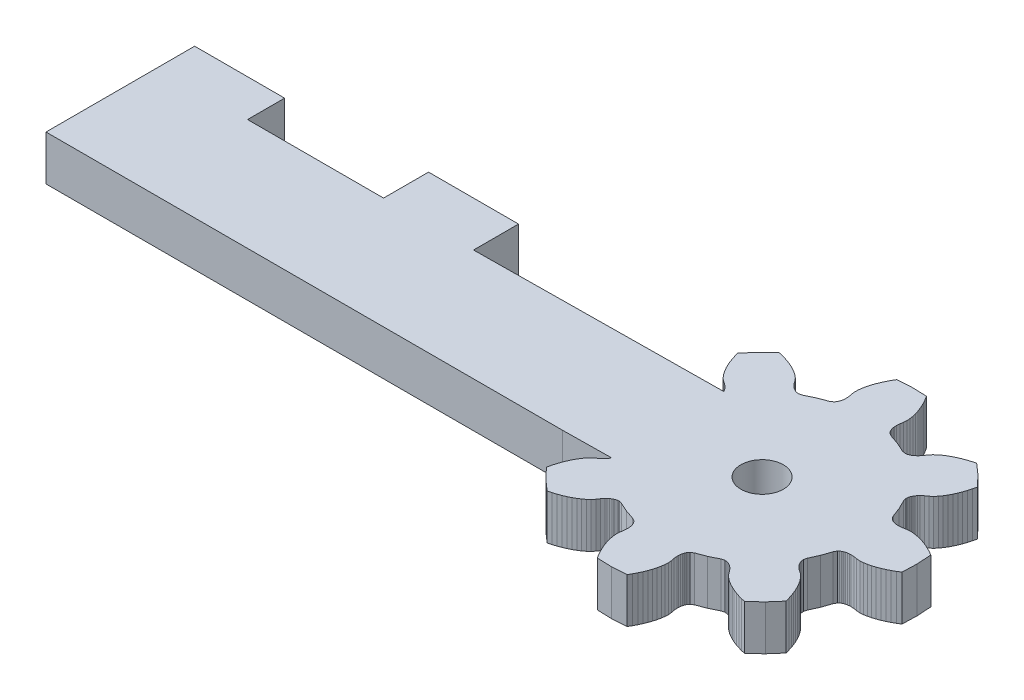
SolidWorks part; units mm, degrees
ref_plane "Front Plane" through (0, 0, 0) normal (0, 0, 1) x (1, 0, 0)
ref_plane "Top Plane" through (0, 0, 0) normal (0, 1, 0) x (1, 0, 0)
ref_plane "Right Plane" through (0, 0, 0) normal (1, 0, 0) x (0, 0, -1)
sketch "Sketch1" plane through (0, 0, 0) normal (0, 1, 0) x (1, 0, 0)
  line L0 (63.4907, 166.1354) -> (63.4907, 169.3104)
  line L1 (63.4907, 169.3104) -> (57.1407, 169.3104)
  line L2 (57.1407, 169.3104) -> (57.1407, 166.1354)
  line L3 (57.1407, 166.1354) -> (47.5407, 166.1354)
  line L4 (47.5407, 166.1354) -> (47.5407, 168.7529)
  line L5 (47.5407, 168.7529) -> (41.1907, 168.7529)
  line L6 (41.1907, 168.7529) -> (41.1907, 158.2613)
  line L7 (41.1907, 158.2613) -> (77.6477, 158.2613)
  line L1268 (81.0578, 158.2714) -> (81.0243, 158.3054)
  line L1269 (81.0243, 158.3054) -> (77.6477, 158.2613)
  line L1276 (63.4907, 166.1354) -> (80.9763, 166.3177)
  line L1277 (80.9763, 166.3177) -> (80.9618, 166.3272)
  line L1278 (80.9618, 166.3272) -> (80.9303, 166.3857)
  line L1279 (80.9303, 166.3857) -> (80.8605, 166.4907)
  line L1280 (80.8605, 166.4907) -> (80.7838, 166.5839)
  line L1281 (80.7838, 166.5839) -> (80.7017, 166.668)
  line L1282 (80.7017, 166.668) -> (80.5246, 166.8149)
  line L1283 (80.5246, 166.8149) -> (80.3334, 166.9392)
  line L1284 (80.3334, 166.9392) -> (80.1557, 167.0849)
  line L1285 (80.1557, 167.0849) -> (79.9967, 167.2599)
  line L1286 (79.9967, 167.2599) -> (79.8501, 167.4532)
  line L1287 (79.8501, 167.4532) -> (79.7145, 167.6617)
  line L1288 (79.7145, 167.6617) -> (79.5894, 167.8837)
  line L1289 (79.5894, 167.8837) -> (79.4745, 168.1179)
  line L1290 (79.4745, 168.1179) -> (79.3699, 168.3635)
  line L1291 (79.3699, 168.3635) -> (79.2754, 168.6197)
  line L1292 (79.2754, 168.6197) -> (79.1915, 168.886)
  line L1293 (79.1915, 168.886) -> (79.1181, 169.1617)
  line L1294 (79.1181, 169.1617) -> (79.8009, 169.9374)
  line L1295 (79.8009, 169.9374) -> (80.5548, 170.6443)
  line L1296 (80.5548, 170.6443) -> (80.8327, 170.5796)
  line L1297 (80.8327, 170.5796) -> (81.1014, 170.504)
  line L1298 (81.1014, 170.504) -> (81.3605, 170.4177)
  line L1299 (81.3605, 170.4177) -> (81.6093, 170.3208)
  line L1300 (81.6093, 170.3208) -> (81.847, 170.2133)
  line L1301 (81.847, 170.2133) -> (82.0728, 170.0952)
  line L1302 (82.0728, 170.0952) -> (82.2854, 169.9663)
  line L1303 (82.2854, 169.9663) -> (82.4832, 169.8259)
  line L1304 (82.4832, 169.8259) -> (82.6631, 169.6724)
  line L1305 (82.6631, 169.6724) -> (82.8144, 169.4994)
  line L1306 (82.8144, 169.4994) -> (82.9446, 169.3122)
  line L1307 (82.9446, 169.3122) -> (83.097, 169.1398)
  line L1308 (83.097, 169.1398) -> (83.1836, 169.0603)
  line L1309 (83.1836, 169.0603) -> (83.2792, 168.9866)
  line L1310 (83.2792, 168.9866) -> (83.3864, 168.9201)
  line L1311 (83.3864, 168.9201) -> (83.4458, 168.8905)
  line L1312 (83.4458, 168.8905) -> (83.5105, 168.8639)
  line L1313 (83.5105, 168.8639) -> (83.5824, 168.8415)
  line L1314 (83.5824, 168.8415) -> (83.6651, 168.8253)
  line L1315 (83.6651, 168.8253) -> (83.768, 168.8205)
  line L1316 (83.768, 168.8205) -> (83.9876, 168.8804)
  line L1317 (83.9876, 168.8804) -> (84.6212, 169.1914)
  line L1318 (84.6212, 169.1914) -> (85.2815, 169.4403)
  line L1319 (85.2815, 169.4403) -> (85.4756, 169.5595)
  line L1320 (85.4756, 169.5595) -> (85.5425, 169.6378)
  line L1321 (85.5425, 169.6378) -> (85.5873, 169.7091)
  line L1322 (85.5873, 169.7091) -> (85.6202, 169.7768)
  line L1323 (85.6202, 169.7768) -> (85.6451, 169.8422)
  line L1324 (85.6451, 169.8422) -> (85.6641, 169.9058)
  line L1325 (85.6641, 169.9058) -> (85.6891, 170.0295)
  line L1326 (85.6891, 170.0295) -> (85.7007, 170.1496)
  line L1327 (85.7007, 170.1496) -> (85.7022, 170.2671)
  line L1328 (85.7022, 170.2671) -> (85.6808, 170.4962)
  line L1329 (85.6808, 170.4962) -> (85.6334, 170.7193)
  line L1330 (85.6334, 170.7193) -> (85.6109, 170.948)
  line L1331 (85.6109, 170.948) -> (85.6222, 171.1842)
  line L1332 (85.6222, 171.1842) -> (85.6552, 171.4245)
  line L1333 (85.6552, 171.4245) -> (85.7068, 171.6678)
  line L1334 (85.7068, 171.6678) -> (85.7752, 171.9132)
  line L1335 (85.7752, 171.9132) -> (85.8596, 172.1601)
  line L1336 (85.8596, 172.1601) -> (85.9593, 172.4078)
  line L1337 (85.9593, 172.4078) -> (86.0737, 172.6557)
  line L1338 (86.0737, 172.6557) -> (86.2026, 172.9034)
  line L1339 (86.2026, 172.9034) -> (86.3457, 173.1502)
  line L1340 (86.3457, 173.1502) -> (87.377, 173.2159)
  line L1341 (87.377, 173.2159) -> (88.4099, 173.1826)
  line L1342 (88.4099, 173.1826) -> (88.5607, 172.9404)
  line L1343 (88.5607, 172.9404) -> (88.6973, 172.6969)
  line L1344 (88.6973, 172.6969) -> (88.8195, 172.4527)
  line L1345 (88.8195, 172.4527) -> (88.9268, 172.2082)
  line L1346 (88.9268, 172.2082) -> (89.0189, 171.9642)
  line L1347 (89.0189, 171.9642) -> (89.0951, 171.721)
  line L1348 (89.0951, 171.721) -> (89.1543, 171.4795)
  line L1349 (89.1543, 171.4795) -> (89.1948, 171.2403)
  line L1350 (89.1948, 171.2403) -> (89.2136, 171.0046)
  line L1351 (89.2136, 171.0046) -> (89.1981, 170.7753)
  line L1352 (89.1981, 170.7753) -> (89.1579, 170.5508)
  line L1353 (89.1579, 170.5508) -> (89.1437, 170.3212)
  line L1354 (89.1437, 170.3212) -> (89.1488, 170.2038)
  line L1355 (89.1488, 170.2038) -> (89.1642, 170.0841)
  line L1356 (89.1642, 170.0841) -> (89.193, 169.9613)
  line L1357 (89.193, 169.9613) -> (89.214, 169.8982)
  line L1358 (89.214, 169.8982) -> (89.241, 169.8337)
  line L1359 (89.241, 169.8337) -> (89.276, 169.7671)
  line L1360 (89.276, 169.7671) -> (89.3231, 169.6971)
  line L1361 (89.3231, 169.6971) -> (89.3924, 169.621)
  line L1362 (89.3924, 169.621) -> (89.59, 169.508)
  line L1363 (89.59, 169.508) -> (90.2579, 169.28)
  line L1364 (90.2579, 169.28) -> (90.9009, 168.989)
  line L1365 (90.9009, 168.989) -> (91.1223, 168.9361)
  line L1366 (91.1223, 168.9361) -> (91.225, 168.9441)
  line L1367 (91.225, 168.9441) -> (91.3072, 168.9629)
  line L1368 (91.3072, 168.9629) -> (91.3783, 168.9875)
  line L1369 (91.3783, 168.9875) -> (91.4422, 169.0161)
  line L1370 (91.4422, 169.0161) -> (91.5006, 169.0476)
  line L1371 (91.5006, 169.0476) -> (91.6057, 169.1174)
  line L1372 (91.6057, 169.1174) -> (91.6989, 169.1941)
  line L1373 (91.6989, 169.1941) -> (91.7829, 169.2762)
  line L1374 (91.7829, 169.2762) -> (91.9298, 169.4533)
  line L1375 (91.9298, 169.4533) -> (92.0541, 169.6445)
  line L1376 (92.0541, 169.6445) -> (92.1999, 169.8223)
  line L1377 (92.1999, 169.8223) -> (92.3749, 169.9812)
  line L1378 (92.3749, 169.9812) -> (92.5682, 170.1278)
  line L1379 (92.5682, 170.1278) -> (92.7767, 170.2634)
  line L1380 (92.7767, 170.2634) -> (92.9986, 170.3885)
  line L1381 (92.9986, 170.3885) -> (93.2328, 170.5034)
  line L1382 (93.2328, 170.5034) -> (93.4784, 170.6081)
  line L1383 (93.4784, 170.6081) -> (93.7347, 170.7025)
  line L1384 (93.7347, 170.7025) -> (94.001, 170.7864)
  line L1385 (94.001, 170.7864) -> (94.2766, 170.8598)
  line L1386 (94.2766, 170.8598) -> (95.0524, 170.177)
  line L1387 (95.0524, 170.177) -> (95.7592, 169.4231)
  line L1388 (95.7592, 169.4231) -> (95.6945, 169.1453)
  line L1389 (95.6945, 169.1453) -> (95.6189, 168.8765)
  line L1390 (95.6189, 168.8765) -> (95.5327, 168.6174)
  line L1391 (95.5327, 168.6174) -> (95.4357, 168.3686)
  line L1392 (95.4357, 168.3686) -> (95.3283, 168.1309)
  line L1393 (95.3283, 168.1309) -> (95.2102, 167.9051)
  line L1394 (95.2102, 167.9051) -> (95.0812, 167.6925)
  line L1395 (95.0812, 167.6925) -> (94.9408, 167.4947)
  line L1396 (94.9408, 167.4947) -> (94.7874, 167.3148)
  line L1397 (94.7874, 167.3148) -> (94.6144, 167.1635)
  line L1398 (94.6144, 167.1635) -> (94.4271, 167.0333)
  line L1399 (94.4271, 167.0333) -> (94.2547, 166.8809)
  line L1400 (94.2547, 166.8809) -> (94.1753, 166.7943)
  line L1401 (94.1753, 166.7943) -> (94.1016, 166.6988)
  line L1402 (94.1016, 166.6988) -> (94.0351, 166.5915)
  line L1403 (94.0351, 166.5915) -> (94.0054, 166.5321)
  line L1404 (94.0054, 166.5321) -> (93.9788, 166.4674)
  line L1405 (93.9788, 166.4674) -> (93.9565, 166.3955)
  line L1406 (93.9565, 166.3955) -> (93.9403, 166.3128)
  line L1407 (93.9403, 166.3128) -> (93.9355, 166.21)
  line L1408 (93.9355, 166.21) -> (93.9954, 165.9903)
  line L1409 (93.9954, 165.9903) -> (94.3064, 165.3568)
  line L1410 (94.3064, 165.3568) -> (94.5553, 164.6964)
  line L1411 (94.5553, 164.6964) -> (94.6744, 164.5024)
  line L1412 (94.6744, 164.5024) -> (94.7527, 164.4354)
  line L1413 (94.7527, 164.4354) -> (94.824, 164.3906)
  line L1414 (94.824, 164.3906) -> (94.8918, 164.3578)
  line L1415 (94.8918, 164.3578) -> (94.9571, 164.3328)
  line L1416 (94.9571, 164.3328) -> (95.0208, 164.3138)
  line L1417 (95.0208, 164.3138) -> (95.1444, 164.2888)
  line L1418 (95.1444, 164.2888) -> (95.2645, 164.2772)
  line L1419 (95.2645, 164.2772) -> (95.382, 164.2758)
  line L1420 (95.382, 164.2758) -> (95.6112, 164.2972)
  line L1421 (95.6112, 164.2972) -> (95.8342, 164.3445)
  line L1422 (95.8342, 164.3445) -> (96.063, 164.3671)
  line L1423 (96.063, 164.3671) -> (96.2992, 164.3557)
  line L1424 (96.2992, 164.3557) -> (96.5395, 164.3227)
  line L1425 (96.5395, 164.3227) -> (96.7828, 164.2712)
  line L1426 (96.7828, 164.2712) -> (97.0282, 164.2027)
  line L1427 (97.0282, 164.2027) -> (97.275, 164.1183)
  line L1428 (97.275, 164.1183) -> (97.5227, 164.0186)
  line L1429 (97.5227, 164.0186) -> (97.7707, 163.9042)
  line L1430 (97.7707, 163.9042) -> (98.0183, 163.7753)
  line L1431 (98.0183, 163.7753) -> (98.2652, 163.6323)
  line L1432 (98.2652, 163.6323) -> (98.3308, 162.6009)
  line L1433 (98.3308, 162.6009) -> (98.2976, 161.568)
  line L1434 (98.2976, 161.568) -> (98.0554, 161.4173)
  line L1435 (98.0554, 161.4173) -> (97.8119, 161.2806)
  line L1436 (97.8119, 161.2806) -> (97.5677, 161.1585)
  line L1437 (97.5677, 161.1585) -> (97.3232, 161.0511)
  line L1438 (97.3232, 161.0511) -> (97.0791, 160.959)
  line L1439 (97.0791, 160.959) -> (96.836, 160.8829)
  line L1440 (96.836, 160.8829) -> (96.5944, 160.8237)
  line L1441 (96.5944, 160.8237) -> (96.3553, 160.7831)
  line L1442 (96.3553, 160.7831) -> (96.1196, 160.7644)
  line L1443 (96.1196, 160.7644) -> (95.8903, 160.7798)
  line L1444 (95.8903, 160.7798) -> (95.6658, 160.8201)
  line L1445 (95.6658, 160.8201) -> (95.4361, 160.8342)
  line L1446 (95.4361, 160.8342) -> (95.3187, 160.8291)
  line L1447 (95.3187, 160.8291) -> (95.199, 160.8137)
  line L1448 (95.199, 160.8137) -> (95.0762, 160.7849)
  line L1449 (95.0762, 160.7849) -> (95.0132, 160.7639)
  line L1450 (95.0132, 160.7639) -> (94.9487, 160.7369)
  line L1451 (94.9487, 160.7369) -> (94.882, 160.7019)
  line L1452 (94.882, 160.7019) -> (94.8121, 160.6549)
  line L1453 (94.8121, 160.6549) -> (94.736, 160.5855)
  line L1454 (94.736, 160.5855) -> (94.623, 160.3879)
  line L1455 (94.623, 160.3879) -> (94.3949, 159.72)
  line L1456 (94.3949, 159.72) -> (94.1039, 159.077)
  line L1457 (94.1039, 159.077) -> (94.051, 158.8556)
  line L1458 (94.051, 158.8556) -> (94.0591, 158.7529)
  line L1459 (94.0591, 158.7529) -> (94.0778, 158.6708)
  line L1460 (94.0778, 158.6708) -> (94.1025, 158.5996)
  line L1461 (94.1025, 158.5996) -> (94.131, 158.5358)
  line L1462 (94.131, 158.5358) -> (94.1626, 158.4773)
  line L1463 (94.1626, 158.4773) -> (94.2324, 158.3722)
  line L1464 (94.2324, 158.3722) -> (94.3091, 158.2791)
  line L1465 (94.3091, 158.2791) -> (94.3912, 158.195)
  line L1466 (94.3912, 158.195) -> (94.5683, 158.0481)
  line L1467 (94.5683, 158.0481) -> (94.7595, 157.9238)
  line L1468 (94.7595, 157.9238) -> (94.9372, 157.778)
  line L1469 (94.9372, 157.778) -> (95.0962, 157.603)
  line L1470 (95.0962, 157.603) -> (95.2427, 157.4097)
  line L1471 (95.2427, 157.4097) -> (95.3783, 157.2013)
  line L1472 (95.3783, 157.2013) -> (95.5035, 156.9793)
  line L1473 (95.5035, 156.9793) -> (95.6184, 156.7451)
  line L1474 (95.6184, 156.7451) -> (95.723, 156.4995)
  line L1475 (95.723, 156.4995) -> (95.8174, 156.2432)
  line L1476 (95.8174, 156.2432) -> (95.9014, 155.9769)
  line L1477 (95.9014, 155.9769) -> (95.9748, 155.7013)
  line L1478 (95.9748, 155.7013) -> (95.292, 154.9255)
  line L1479 (95.292, 154.9255) -> (94.5381, 154.2187)
  line L1480 (94.5381, 154.2187) -> (94.2602, 154.2834)
  line L1481 (94.2602, 154.2834) -> (93.9914, 154.359)
  line L1482 (93.9914, 154.359) -> (93.7324, 154.4453)
  line L1483 (93.7324, 154.4453) -> (93.4836, 154.5422)
  line L1484 (93.4836, 154.5422) -> (93.2458, 154.6496)
  line L1485 (93.2458, 154.6496) -> (93.0201, 154.7677)
  line L1486 (93.0201, 154.7677) -> (92.8074, 154.8967)
  line L1487 (92.8074, 154.8967) -> (92.6097, 155.0371)
  line L1488 (92.6097, 155.0371) -> (92.4297, 155.1905)
  line L1489 (92.4297, 155.1905) -> (92.2785, 155.3636)
  line L1490 (92.2785, 155.3636) -> (92.1482, 155.5508)
  line L1491 (92.1482, 155.5508) -> (91.9959, 155.7232)
  line L1492 (91.9959, 155.7232) -> (91.9092, 155.8026)
  line L1493 (91.9092, 155.8026) -> (91.8137, 155.8763)
  line L1494 (91.8137, 155.8763) -> (91.7065, 155.9428)
  line L1495 (91.7065, 155.9428) -> (91.6471, 155.9725)
  line L1496 (91.6471, 155.9725) -> (91.5824, 155.9991)
  line L1497 (91.5824, 155.9991) -> (91.5105, 156.0215)
  line L1498 (91.5105, 156.0215) -> (91.4278, 156.0376)
  line L1499 (91.4278, 156.0376) -> (91.3249, 156.0424)
  line L1500 (91.3249, 156.0424) -> (91.1052, 155.9826)
  line L1501 (91.1052, 155.9826) -> (90.4717, 155.6716)
  line L1502 (90.4717, 155.6716) -> (89.8113, 155.4226)
  line L1503 (89.8113, 155.4226) -> (89.6173, 155.3035)
  line L1504 (89.6173, 155.3035) -> (89.5504, 155.2252)
  line L1505 (89.5504, 155.2252) -> (89.5056, 155.1539)
  line L1506 (89.5056, 155.1539) -> (89.4727, 155.0862)
  line L1507 (89.4727, 155.0862) -> (89.4478, 155.0208)
  line L1508 (89.4478, 155.0208) -> (89.4287, 154.9571)
  line L1509 (89.4287, 154.9571) -> (89.4038, 154.8335)
  line L1510 (89.4038, 154.8335) -> (89.3921, 154.7134)
  line L1511 (89.3921, 154.7134) -> (89.3907, 154.5959)
  line L1512 (89.3907, 154.5959) -> (89.4121, 154.3667)
  line L1513 (89.4121, 154.3667) -> (89.4594, 154.1437)
  line L1514 (89.4594, 154.1437) -> (89.482, 153.9149)
  line L1515 (89.482, 153.9149) -> (89.4707, 153.6788)
  line L1516 (89.4707, 153.6788) -> (89.4377, 153.4385)
  line L1517 (89.4377, 153.4385) -> (89.3861, 153.1952)
  line L1518 (89.3861, 153.1952) -> (89.3176, 152.9497)
  line L1519 (89.3176, 152.9497) -> (89.2332, 152.7029)
  line L1520 (89.2332, 152.7029) -> (89.1336, 152.4552)
  line L1521 (89.1336, 152.4552) -> (89.0191, 152.2072)
  line L1522 (89.0191, 152.2072) -> (88.8903, 151.9596)
  line L1523 (88.8903, 151.9596) -> (88.7472, 151.7128)
  line L1524 (88.7472, 151.7128) -> (87.7159, 151.6471)
  line L1525 (87.7159, 151.6471) -> (86.6829, 151.6804)
  line L1526 (86.6829, 151.6804) -> (86.5322, 151.9226)
  line L1527 (86.5322, 151.9226) -> (86.3956, 152.166)
  line L1528 (86.3956, 152.166) -> (86.2734, 152.4103)
  line L1529 (86.2734, 152.4103) -> (86.166, 152.6547)
  line L1530 (86.166, 152.6547) -> (86.0739, 152.8988)
  line L1531 (86.0739, 152.8988) -> (85.9978, 153.1419)
  line L1532 (85.9978, 153.1419) -> (85.9386, 153.3835)
  line L1533 (85.9386, 153.3835) -> (85.8981, 153.6226)
  line L1534 (85.8981, 153.6226) -> (85.8793, 153.8584)
  line L1535 (85.8793, 153.8584) -> (85.8947, 154.0877)
  line L1536 (85.8947, 154.0877) -> (85.935, 154.3121)
  line L1537 (85.935, 154.3121) -> (85.9492, 154.5418)
  line L1538 (85.9492, 154.5418) -> (85.9441, 154.6592)
  line L1539 (85.9441, 154.6592) -> (85.9287, 154.7789)
  line L1540 (85.9287, 154.7789) -> (85.8999, 154.9017)
  line L1541 (85.8999, 154.9017) -> (85.8788, 154.9647)
  line L1542 (85.8788, 154.9647) -> (85.8518, 155.0293)
  line L1543 (85.8518, 155.0293) -> (85.8168, 155.0959)
  line L1544 (85.8168, 155.0959) -> (85.7698, 155.1658)
  line L1545 (85.7698, 155.1658) -> (85.7005, 155.242)
  line L1546 (85.7005, 155.242) -> (85.5028, 155.3549)
  line L1547 (85.5028, 155.3549) -> (84.8349, 155.583)
  line L1548 (84.8349, 155.583) -> (84.1919, 155.874)
  line L1549 (84.1919, 155.874) -> (83.9705, 155.9269)
  line L1550 (83.9705, 155.9269) -> (83.8679, 155.9189)
  line L1551 (83.8679, 155.9189) -> (83.7857, 155.9001)
  line L1552 (83.7857, 155.9001) -> (83.7146, 155.8755)
  line L1553 (83.7146, 155.8755) -> (83.6507, 155.8469)
  line L1554 (83.6507, 155.8469) -> (83.5922, 155.8153)
  line L1555 (83.5922, 155.8153) -> (83.4872, 155.7456)
  line L1556 (83.4872, 155.7456) -> (83.394, 155.6689)
  line L1557 (83.394, 155.6689) -> (83.3099, 155.5868)
  line L1558 (83.3099, 155.5868) -> (83.163, 155.4096)
  line L1559 (83.163, 155.4096) -> (83.0388, 155.2184)
  line L1560 (83.0388, 155.2184) -> (82.893, 155.0407)
  line L1561 (82.893, 155.0407) -> (82.718, 154.8817)
  line L1562 (82.718, 154.8817) -> (82.5247, 154.7352)
  line L1563 (82.5247, 154.7352) -> (82.3162, 154.5996)
  line L1564 (82.3162, 154.5996) -> (82.0943, 154.4745)
  line L1565 (82.0943, 154.4745) -> (81.86, 154.3596)
  line L1566 (81.86, 154.3596) -> (81.6144, 154.2549)
  line L1567 (81.6144, 154.2549) -> (81.3582, 154.1605)
  line L1568 (81.3582, 154.1605) -> (81.0919, 154.0765)
  line L1569 (81.0919, 154.0765) -> (80.8162, 154.0031)
  line L1570 (80.8162, 154.0031) -> (80.0405, 154.686)
  line L1571 (80.0405, 154.686) -> (79.3336, 155.4399)
  line L1572 (79.3336, 155.4399) -> (79.3983, 155.7177)
  line L1573 (79.3983, 155.7177) -> (79.4739, 155.9865)
  line L1574 (79.4739, 155.9865) -> (79.5602, 156.2456)
  line L1575 (79.5602, 156.2456) -> (79.6571, 156.4943)
  line L1576 (79.6571, 156.4943) -> (79.7646, 156.7321)
  line L1577 (79.7646, 156.7321) -> (79.8827, 156.9578)
  line L1578 (79.8827, 156.9578) -> (80.0116, 157.1705)
  line L1579 (80.0116, 157.1705) -> (80.1521, 157.3682)
  line L1580 (80.1521, 157.3682) -> (80.3055, 157.5482)
  line L1581 (80.3055, 157.5482) -> (80.4785, 157.6995)
  line L1582 (80.4785, 157.6995) -> (80.6657, 157.8297)
  line L1583 (80.6657, 157.8297) -> (80.8382, 157.9821)
  line L1584 (80.8382, 157.9821) -> (80.9176, 158.0687)
  line L1585 (80.9176, 158.0687) -> (80.9913, 158.1642)
  line L1586 (80.9913, 158.1642) -> (81.0578, 158.2714)
  circle A0 centre (87.5463, 162.4441) radius 1.5001
  dimension "D1" = 6.35
  dimension "D2" = 3.175
  dimension "D3" = 6.35
  dimension "D4" = 9.6
extrude "Boss-Extrude1" add sketch "Sketch1" along normal blind 3.175
